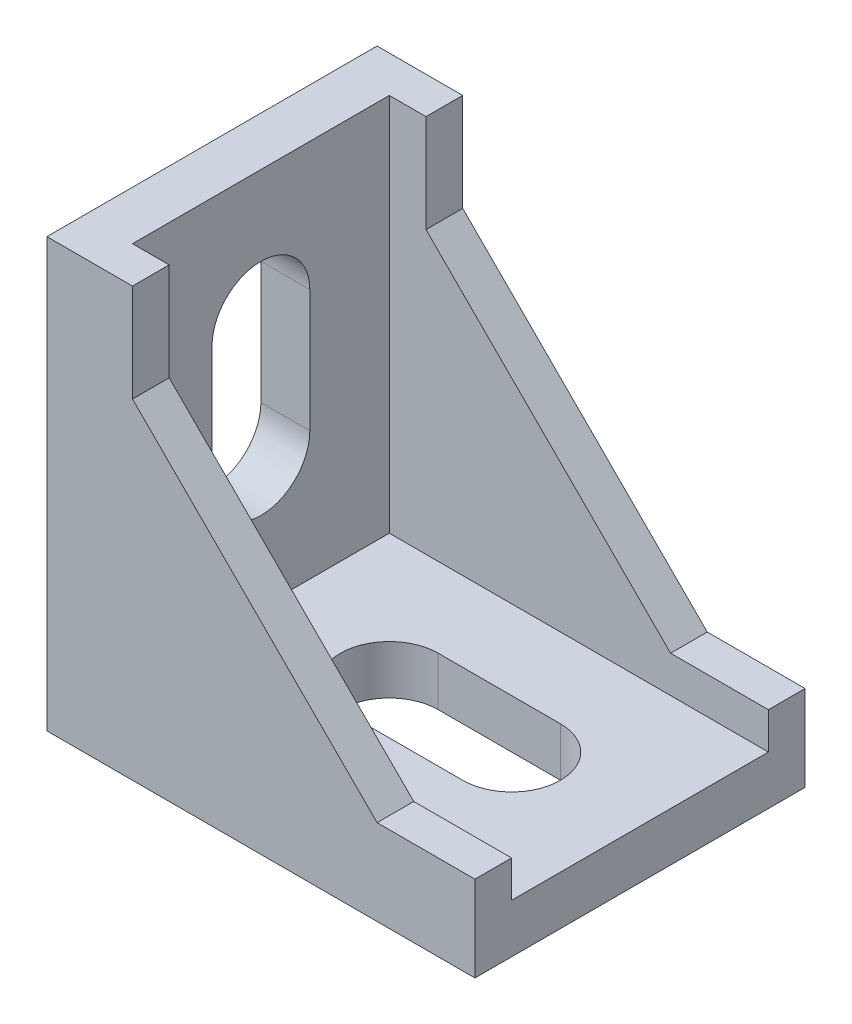
SolidWorks part; units mm, degrees
ref_plane "Front Plane" through (0, 0, 0) normal (0, 0, 1) x (1, 0, 0)
ref_plane "Top Plane" through (0, 0, 0) normal (0, 1, 0) x (1, 0, 0)
ref_plane "Right Plane" through (0, 0, 0) normal (1, 0, 0) x (0, 0, -1)
sketch "Sketch1" plane through (0, 0, 0) normal (0, 0, 1) x (1, 0, 0)
  line L1 (-17.5, 17.5) -> (17.5, 17.5)
  line L2 (-17.5, 17.5) -> (-17.5, -17.5)
  line L3 (-17.5, -17.5) -> (17.5, -17.5)
  line L4 (17.5, 17.5) -> (17.5, -17.5)
  line L5 (-17.5, 17.5) -> (17.5, -17.5) construction
  line L6 (-17.5, -17.5) -> (17.5, 17.5) construction
  point P0 (0, 0)
  dimension "D1" = 35
  dimension "D2" = 35
extrude "Boss-Extrude1" add sketch "Sketch1" along normal blind 27
sketch "Sketch2" plane through (0, 17.5, 0) normal (0, 1, 0) x (1, 0, 0)
  line L0 (-17.5, -27) -> (-17.5, 0) construction
  line L1 (17.5, -3) -> (-13.5, -3)
  line L2 (17.5, -3) -> (17.5, -24)
  line L3 (17.5, -24) -> (-13.5, -24)
  line L4 (-13.5, -3) -> (-13.5, -24)
  line L5 (17.5, -3) -> (-13.5, -24) construction
  line L6 (17.5, -24) -> (-13.5, -3) construction
  line L7 (17.5, 0) -> (-17.5, 0) construction
  line L8 (17.5, -27) -> (-17.5, -27) construction
  point P0 (2, -13.5)
  dimension "D1" = 4
  dimension "D2" = 3
  dimension "D3" = 3
  dimension "D4" = 31
extrude "Cut-Extrude1" cut sketch "Sketch2" against normal blind 31
sketch "Sketch3" plane through (0, 0, 27) normal (0, 0, 1) x (1, 0, 0)
  line L0 (-17.5, 17.5) -> (-17.5, -17.5) construction
  line L1 (17.5, 17.5) -> (-10.5, 17.5)
  line L2 (17.5, 17.5) -> (17.5, -10.5)
  line L3 (17.5, -10.5) -> (9.5, -10.5)
  line L4 (-10.5, 17.5) -> (-10.5, 9.5)
  line L5 (-17.5, -17.5) -> (17.5, -17.5) construction
  line L6 (-10.5, 9.5) -> (9.5, -10.5)
  line L7 (17.5, -17.5) -> (17.5, 17.5) construction
  dimension "D1" = 7
  dimension "D2" = 7
  dimension "D3" = 8
  dimension "D4" = 8
extrude "Cut-Extrude2" cut sketch "Sketch3" against normal through all
sketch "Sketch4" plane through (-13.5, 0, 0) normal (1, 0, 0) x (0, 0, -1)
  line L0 (-13.5, 7) -> (-13.5, -3) construction
  line L1 (-9.5, 7) -> (-9.5, -3)
  line L2 (-17.5, 7) -> (-17.5, -3)
  line L4 (-3, -13.5) -> (-3, 17.5) construction
  line L6 (-3, 17.5) -> (-24, 17.5) construction
  arc A0 (-9.5, 7) -> (-17.5, 7) centre (-13.5, 7) ccw
  arc A1 (-17.5, -3) -> (-9.5, -3) centre (-13.5, -3) ccw
  point P2 (-13.5, 2)
  point P11 (-13.5, -7)
  point P12 (-13.5, 11)
  dimension "D2" = 4
  dimension "D1" = 10.5
  dimension "D3" = 15.5
  dimension "D4" = 18
extrude "Cut-Extrude3" cut sketch "Sketch4" against normal through all
sketch "Sketch5" plane through (0, -13.5, 0) normal (0, 1, 0) x (1, 0, 0)
  line L0 (-3, -13.5) -> (7, -13.5) construction
  line L1 (-3, -9.5) -> (7, -9.5)
  line L2 (-3, -17.5) -> (7, -17.5)
  line L3 (-13.5, -24) -> (17.5, -24) construction
  line L4 (17.5, -24) -> (17.5, -3) construction
  arc A0 (-3, -9.5) -> (-3, -17.5) centre (-3, -13.5) ccw
  arc A1 (7, -17.5) -> (7, -9.5) centre (7, -13.5) ccw
  point P2 (2, -13.5)
  point P12 (11, -13.5)
  point P13 (-7, -13.5)
  dimension "D2" = 18
  dimension "D4" = 4
  dimension "D1" = 10.5
  dimension "D3" = 15.5
extrude "Cut-Extrude4" cut sketch "Sketch5" against normal through all
sketch "Sketch7" plane through (0, -17.5, 0) normal (0, -1, 0) x (1, 0, 0)
  line L0 (-17.5, 27) -> (17.5, 27) construction
  line L1 (-15.5, 24) -> (15.5, 24)
  line L2 (-15.5, 24) -> (-15.5, 20.5)
  line L3 (-15.5, 20.5) -> (15.5, 20.5)
  line L4 (15.5, 24) -> (15.5, 20.5)
  line L5 (17.5, 27) -> (17.5, 0) construction
  line L6 (-17.5, 27) -> (-17.5, 0) construction
  line L7 (-3, 17.5) -> (7, 17.5) construction
  dimension "D1" = 3
  dimension "D2" = 2
  dimension "D3" = 2
  dimension "D4" = 3
extrude "Cut-Extrude5" cut sketch "Sketch7" against normal blind 1
sketch "Sketch8" plane through (0, -17.5, 0) normal (0, -1, 0) x (1, 0, 0)
  line L0 (-17.5, 27) -> (-17.5, 0) construction
  line L1 (-15.5, 6.5) -> (15.5, 6.5)
  line L2 (-15.5, 6.5) -> (-15.5, 3)
  line L3 (-15.5, 3) -> (15.5, 3)
  line L4 (15.5, 6.5) -> (15.5, 3)
  line L5 (17.5, 27) -> (17.5, 0) construction
  line L6 (-17.5, 0) -> (17.5, 0) construction
  line L7 (7, 9.5) -> (-3, 9.5) construction
  dimension "D1" = 2
  dimension "D2" = 2
  dimension "D3" = 3
  dimension "D4" = 3
extrude "Cut-Extrude6" cut sketch "Sketch8" against normal blind 1
sketch "Sketch9" plane through (-17.5, 0, 0) normal (-1, 0, 0) x (0, 0, 1)
  line L0 (27, 17.5) -> (0, 17.5) construction
  line L1 (20.5, 15.5) -> (24, 15.5)
  line L2 (20.5, 15.5) -> (20.5, -15.5)
  line L3 (20.5, -15.5) -> (24, -15.5)
  line L4 (24, 15.5) -> (24, -15.5)
  line L5 (27, -17.5) -> (0, -17.5) construction
  line L6 (27, 17.5) -> (27, -17.5) construction
  line L7 (17.5, 7) -> (17.5, -3) construction
  dimension "D1" = 2
  dimension "D2" = 3
  dimension "2" = 2
  dimension "D3" = 3
extrude "Cut-Extrude13" cut sketch "Sketch9" against normal blind 1
sketch "Sketch10" plane through (-17.5, 0, 0) normal (-1, 0, 0) x (0, 0, 1)
  line L0 (27, 17.5) -> (0, 17.5) construction
  line L1 (3, 15.5) -> (6.5, 15.5)
  line L2 (3, 15.5) -> (3, -15.5)
  line L3 (3, -15.5) -> (6.5, -15.5)
  line L4 (6.5, 15.5) -> (6.5, -15.5)
  line L5 (27, -17.5) -> (0, -17.5) construction
  line L6 (9.5, -3) -> (9.5, 7) construction
  line L7 (0, 17.5) -> (0, -17.5) construction
  dimension "D1" = 2
  dimension "D2" = 2
  dimension "D3" = 3
  dimension "D4" = 3
extrude "Cut-Extrude14" cut sketch "Sketch10" against normal blind 1
